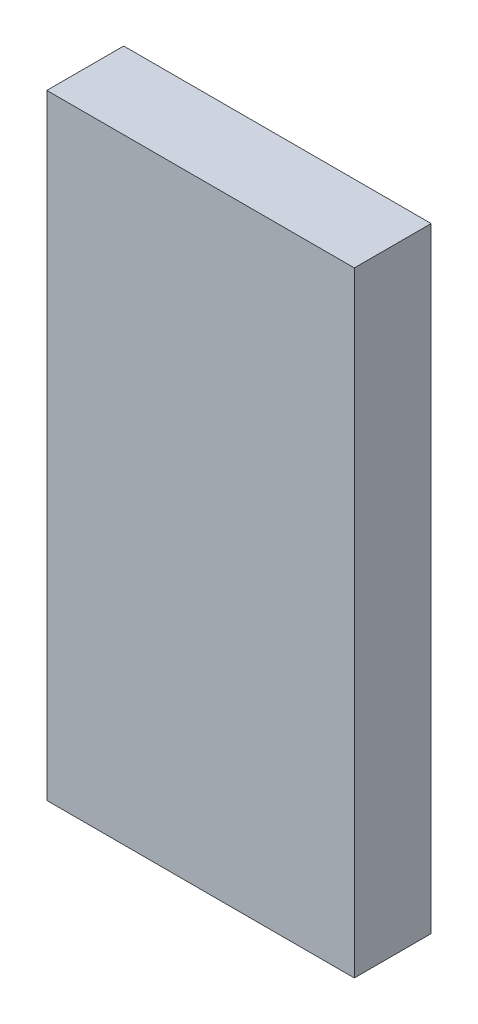
SolidWorks part; units mm, degrees
ref_plane "Front Plane" through (0, 0, 0) normal (0, 0, 1) x (1, 0, 0)
ref_plane "Top Plane" through (0, 0, 0) normal (0, 1, 0) x (1, 0, 0)
ref_plane "Right Plane" through (0, 0, 0) normal (1, 0, 0) x (0, 0, -1)
sketch "Sketch1" plane through (0, 0, 0) normal (0, 0, 1) x (1, 0, 0)
  line L1 (-5, 10) -> (5, 10)
  line L2 (-5, 10) -> (-5, -10)
  line L3 (-5, -10) -> (5, -10)
  line L4 (5, 10) -> (5, -10)
  line L5 (-5, 10) -> (5, -10) construction
  line L6 (-5, -10) -> (5, 10) construction
  point P0 (0, 0)
  dimension "D1" = 10
  dimension "D2" = 20
extrude "Boss-Extrude1" add sketch "Sketch1" along normal blind 2.5
